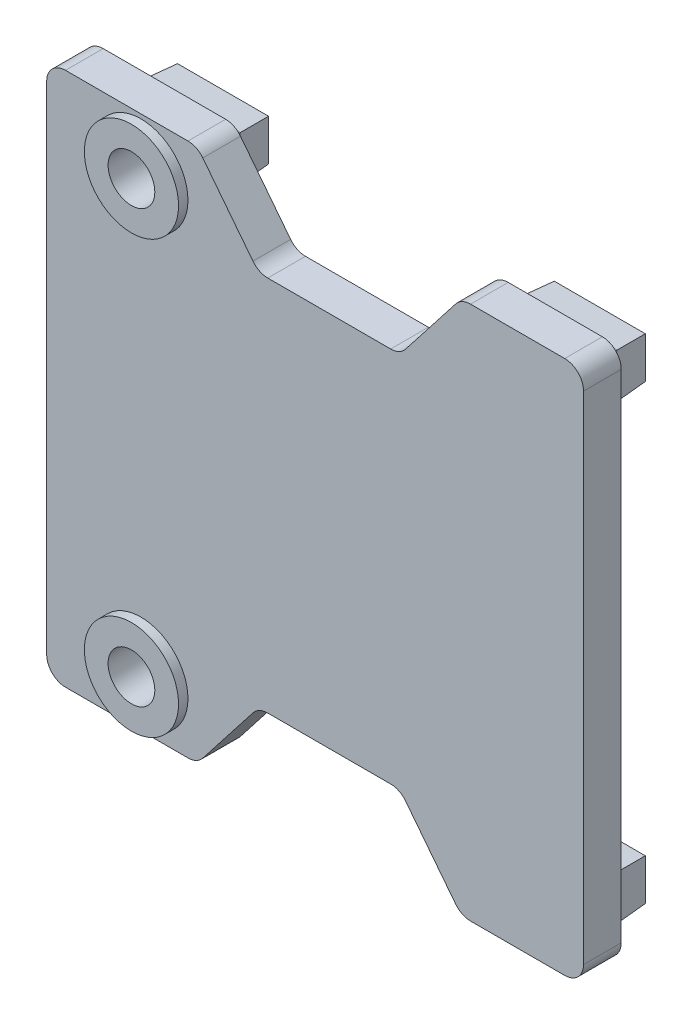
SolidWorks part; units mm, degrees
ref_plane "Front Plane" through (0, 0, 0) normal (0, 0, 1) x (1, 0, 0)
ref_plane "Top Plane" through (0, 0, 0) normal (0, 1, 0) x (1, 0, 0)
ref_plane "Right Plane" through (0, 0, 0) normal (1, 0, 0) x (0, 0, -1)
sketch "Sketch1" plane through (0, 0, 0) normal (0, 0, 1) x (1, 0, 0)
  line L0 (190.5, 35.0834) -> (-190.5, -35.0834) construction
  line L1 (190.5, -25.4) -> (-190.5, -25.4) construction
  line L2 (190.5, -25.4) -> (190.5, 25.4) construction
  line L3 (190.5, 25.4) -> (-190.5, 25.4) construction
  line L4 (-190.5, -25.4) -> (-190.5, 16.74) construction
  line L5 (190.5, -25.4) -> (-190.5, 25.4) construction
  line L6 (190.5, 25.4) -> (-190.5, -25.4) construction
  line L7 (-190.5, 20.09) -> (190.5, 20.09) construction
  line L8 (-184.15, 18.01) -> (-180.975, 18.01)
  line L9 (178.0459, 12.7) -> (-197.2145, 12.7) construction
  line L10 (-179.9737, 17.5212) -> (-176.5938, 13.1888)
  line L11 (-166.3062, 13.1888) -> (-162.9263, 17.5212)
  line L12 (-161.925, 18.01) -> (-155.575, 18.01)
  line L13 (-154.305, 16.74) -> (-154.305, 0)
  line L14 (0, 0) -> (-190.5, 0) construction
  line L15 (-154.305, 0) -> (-190.5, 0)
  line L16 (-190.5, 0) -> (-190.5, 16.74)
  line L17 (-175.5925, 12.7) -> (-167.3075, 12.7)
  line L18 (-184.15, 18.01) -> (-189.23, 18.01)
  line L19 (-155.575, 16.74) -> (-161.925, 16.74) construction
  line L20 (-155.575, 16.74) -> (-155.575, 13.74) construction
  line L21 (-155.575, 13.74) -> (-161.925, 13.74) construction
  line L22 (-161.925, 16.74) -> (-161.925, 13.74) construction
  line L23 (-155.575, 16.74) -> (-161.925, 13.74) construction
  line L24 (-155.575, 13.74) -> (-161.925, 16.74) construction
  line L25 (-190.5, 19.2281) -> (-190.5, 16.74) construction
  line L26 (-190.5, 16.74) -> (-190.5, 19.2281) construction
  line L27 (-180.975, 16.74) -> (-187.325, 16.74) construction
  line L28 (-180.975, 16.74) -> (-180.975, 13.74) construction
  line L29 (-180.975, 13.74) -> (-187.325, 13.74) construction
  line L30 (-187.325, 16.74) -> (-187.325, 13.74) construction
  line L31 (-180.975, 16.74) -> (-187.325, 13.74) construction
  line L32 (-180.975, 13.74) -> (-187.325, 16.74) construction
  line L33 (-190.5, 19.2281) -> (-190.5, 25.4) construction
  line L34 (-190.5, 16.74) -> (-190.5, 19.2281) construction
  circle A0 centre (-184.15, 14.5464) radius 5.5436 construction
  circle A1 centre (-184.15, 14.5464) radius 4.5 construction
  circle A2 centre (-184.15, 14.5464) radius 1.575
  circle A3 centre (-184.15, 14.5464) radius 3.175 construction
  arc A4 (-175.5925, 12.7) -> (-176.5938, 13.1888) centre (-175.5925, 13.97) cw
  arc A5 (-167.3075, 12.7) -> (-166.3062, 13.1888) centre (-167.3075, 13.97) ccw
  arc A6 (-162.9263, 17.5212) -> (-161.925, 18.01) centre (-161.925, 16.74) cw
  arc A7 (-154.305, 16.74) -> (-155.575, 18.01) centre (-155.575, 16.74) ccw
  arc A8 (-179.9737, 17.5212) -> (-180.975, 18.01) centre (-180.975, 16.74) ccw
  arc A9 (-189.23, 18.01) -> (-190.5, 16.74) centre (-189.23, 16.74) ccw
  point P0 (0, 0)
  point P27 (-158.75, 15.24)
  point P37 (-176.2125, 12.7)
  point P40 (-166.6875, 12.7)
  point P46 (-176.2125, 12.7)
  point P51 (-190.5, 18.01)
  point P54 (-184.15, 15.24)
  point P61 (-171.45, 12.7)
  dimension "D3" = 9
  dimension "D4" = 11.0871
  dimension "D6" = 3.15
  dimension "D7" = 6.35
  dimension "D14" = 1.27
  dimension "D1" = 50.8
  dimension "D2" = 5.31
  dimension "D5" = 6.35
  dimension "D8" = 9.525
  dimension "D9" = 19.05
  dimension "D10" = 3
  dimension "D11" = 6.35
  dimension "D12" = 15.24
  dimension "D13" = 31.75
  dimension "D15" = 6.35
  dimension "D16" = 6.35
  dimension "D17" = 3
  dimension "D18" = 381
  dimension "D21" = 12.7
extrude "Boss-Extrude1" add sketch "Sketch1" along normal blind 2.54
sketch "Sketch2" plane through (0, 0, 2.54) normal (0, 0, 1) x (1, 0, 0)
  circle A0 centre (-184.15, 14.5464) radius 1.575
  circle A1 centre (-184.15, 14.5464) radius 3.175
  circle A2 centre (-184.15, 14.5464) radius 1.575 construction
  dimension "D1" = 6.35
extrude "Boss-Extrude2" add sketch "Sketch2" along normal offset from surface (0.635 mm away) 3.175 up to face at (-171.8582, 13.7761, 0)
sketch "Sketch3" plane through (0, 0, 0) normal (0, 0, -1) x (-1, 0, 0)
  line L0 (0, 0) -> (197.0263, 0) construction
  line L1 (187.325, 13.74) -> (180.975, 13.74)
  line L2 (187.325, 13.74) -> (187.325, 16.74)
  line L3 (187.325, 16.74) -> (180.975, 16.74)
  line L4 (180.975, 13.74) -> (180.975, 16.74)
  line L5 (187.325, 13.74) -> (180.975, 16.74) construction
  line L6 (187.325, 16.74) -> (180.975, 13.74) construction
  line L7 (161.925, 13.74) -> (155.575, 13.74)
  line L8 (161.925, 13.74) -> (161.925, 16.74)
  line L9 (161.925, 16.74) -> (155.575, 16.74)
  line L10 (155.575, 13.74) -> (155.575, 16.74)
  line L11 (161.925, 13.74) -> (155.575, 16.74) construction
  line L12 (161.925, 16.74) -> (155.575, 13.74) construction
  line L13 (-190.5, 25.4) -> (190.5, -25.4) construction
  point P0 (184.15, 15.24)
  point P5 (158.75, 15.24)
  dimension "D1" = 6.35
  dimension "D2" = 3
  dimension "D3" = 15.24
  dimension "D4" = 25.4
  dimension "D5" = 6.35
extrude "Boss-Extrude3" add sketch "Sketch3" along normal blind 1
sketch "Sketch4" plane through (0, 0, -1) normal (0, 0, -1) x (-1, 0, 0)
  line L0 (180.975, 16.74) -> (180.975, 13.74) construction
  line L1 (180.975, 13.74) -> (187.325, 13.74) construction
  line L2 (187.325, 13.74) -> (187.325, 16.74) construction
  line L3 (187.325, 16.74) -> (180.975, 16.74) construction
  line L4 (155.575, 16.74) -> (155.575, 13.74) construction
  line L5 (155.575, 13.74) -> (161.925, 13.74) construction
  line L6 (161.925, 13.74) -> (161.925, 16.74) construction
  line L7 (161.925, 16.74) -> (155.575, 16.74) construction
  line L8 (180.975, 16.74) -> (180.975, 13.74)
  line L9 (180.975, 13.74) -> (187.325, 13.74)
  line L10 (187.325, 13.74) -> (187.325, 16.74)
  line L11 (187.325, 16.74) -> (180.975, 16.74)
  line L12 (155.575, 16.74) -> (155.575, 13.74)
  line L13 (155.575, 13.74) -> (161.925, 13.74)
  line L14 (161.925, 13.74) -> (161.925, 16.74)
  line L15 (161.925, 16.74) -> (155.575, 16.74)
extrude "Boss-Extrude4" add sketch "Sketch4" along normal offset from surface 3 draft 3
mirror "Mirror1" about plane through (0, 0, 0) normal (0, 1, 0) of bodies 105 102
